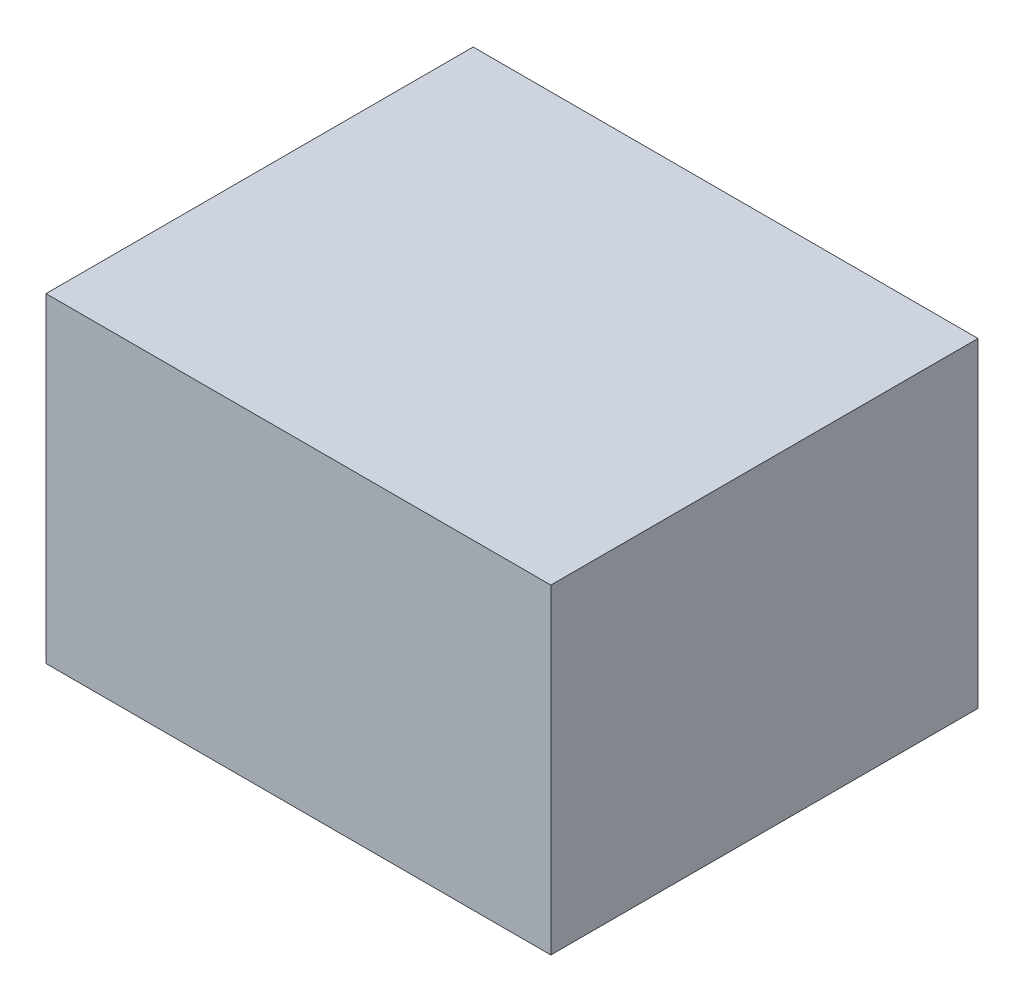
SolidWorks part; units mm, degrees
ref_plane "Front Plane" through (0, 0, 0) normal (0, 0, 1) x (1, 0, 0)
ref_plane "Top Plane" through (0, 0, 0) normal (0, 1, 0) x (1, 0, 0)
ref_plane "Right Plane" through (0, 0, 0) normal (1, 0, 0) x (0, 0, -1)
sketch "Sketch1" plane through (0, 0, 0) normal (0, 1, 0) x (1, 0, 0)
  line L1 (0, 0) -> (6.604, 0)
  line L2 (0, 0) -> (0, 5.588)
  line L3 (0, 5.588) -> (6.604, 5.588)
  line L4 (6.604, 0) -> (6.604, 5.588)
  dimension "D1" = 5.588
  dimension "D2" = 6.604
extrude "Extrude1" add sketch "Sketch1" along normal blind 4.191
